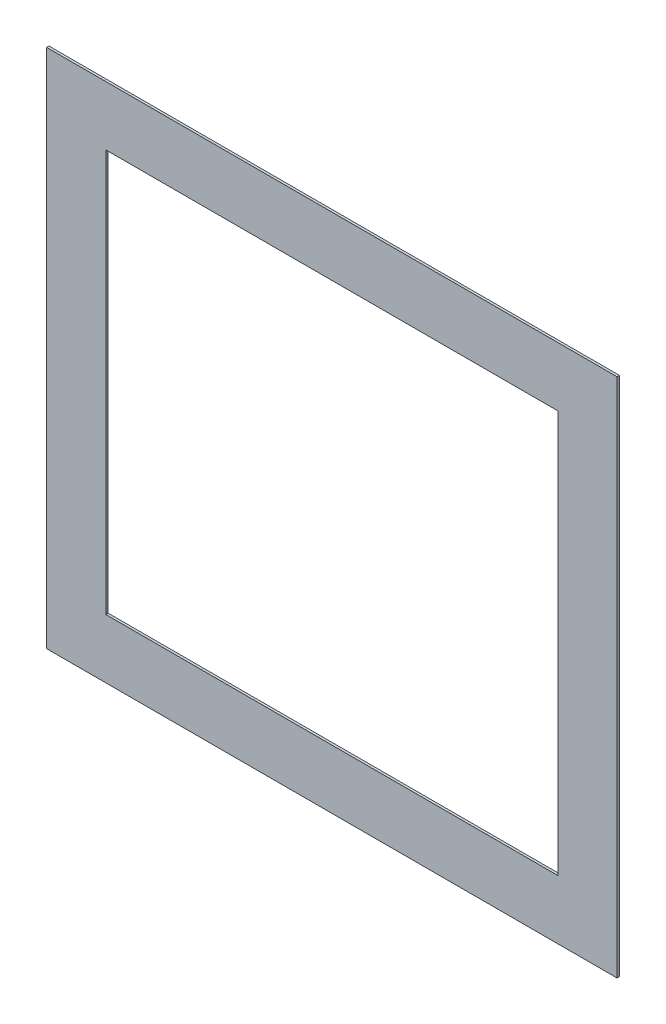
SolidWorks part; units mm, degrees
ref_plane "정면" through (0, 0, 0) normal (0, 0, 1) x (1, 0, 0)
ref_plane "윗면" through (0, 0, 0) normal (0, 1, 0) x (1, 0, 0)
ref_plane "우측면" through (0, 0, 0) normal (1, 0, 0) x (0, 0, -1)
sketch "스케치1" plane through (0, 0, 0) normal (0, 0, 1) x (1, 0, 0)
  line L0 (5, 5) -> (43.2, 5)
  line L1 (0, 0) -> (48.2, 0)
  line L2 (0, 0) -> (0, 44)
  line L3 (0, 44) -> (48.2, 44)
  line L4 (48.2, 0) -> (48.2, 44)
  line L5 (43.2, 5) -> (43.2, 39)
  line L6 (5, 39) -> (43.2, 39)
  line L7 (5, 5) -> (5, 39)
  dimension "D1" = 48.2
  dimension "D2" = 44
  dimension "D3" = 5
extrude "보스-돌출1" add sketch "스케치1" along normal blind 0.2
